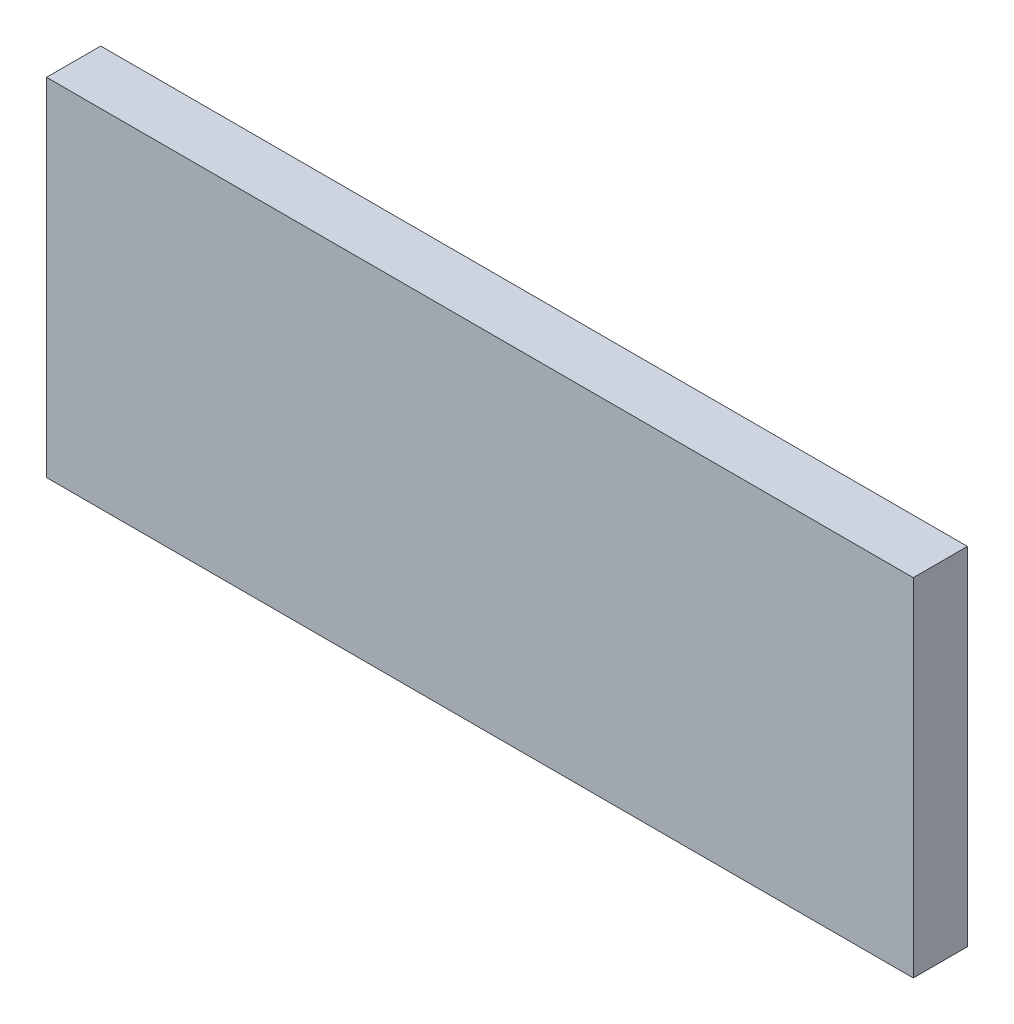
SolidWorks part; units mm, degrees
ref_plane "Front Plane" through (0, 0, 0) normal (1, 0, 0) x (0, 1, 0)
ref_plane "Top Plane" through (0, 0, 0) normal (0, 0, 1) x (0, 1, 0)
ref_plane "Right Plane" through (0, 0, 0) normal (0, 1, 0) x (-1, 0, 0)
sketch "Sketch1" plane through (0, 0, 0) normal (0, 0, 1) x (0, 1, 0)
  line L1 (-16, -40) -> (16, -40)
  line L2 (-16, -40) -> (-16, 40)
  line L3 (-16, 40) -> (16, 40)
  line L4 (16, -40) -> (16, 40)
  line L5 (-16, -40) -> (16, 40) construction
  line L6 (-16, 40) -> (16, -40) construction
  point P0 (0, 0)
  dimension "D1" = 32
  dimension "D2" = 80
extrude "Boss-Extrude1" add sketch "Sketch1" along normal blind 5
